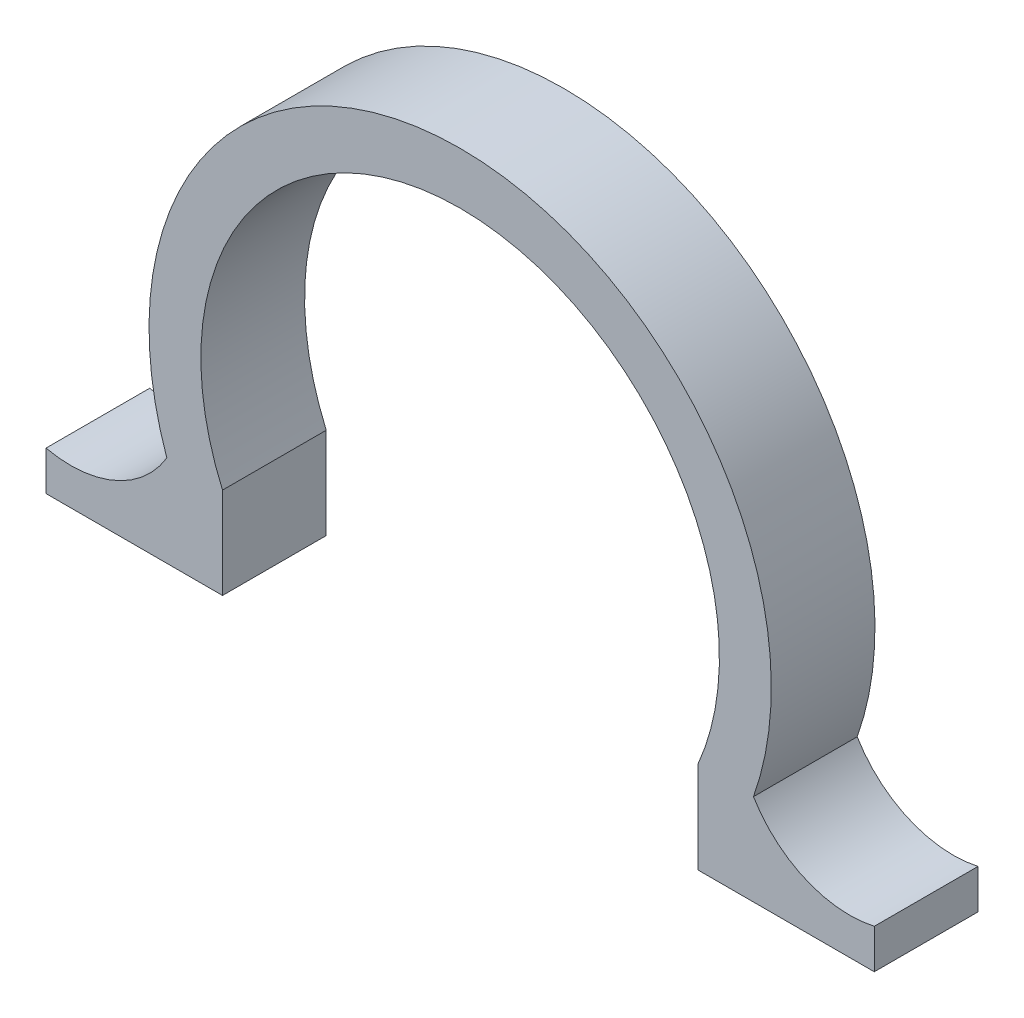
SolidWorks part; units mm, degrees
material "PE High Density"
ref_plane "Front Plane" through (0, 0, 0) normal (0, 0, 1) x (1, 0, 0)
ref_plane "Top Plane" through (0, 0, 0) normal (0, 1, 0) x (1, 0, 0)
ref_plane "Right Plane" through (0, 0, 0) normal (1, 0, 0) x (0, 0, -1)
sketch "Sketch3" plane through (0, 0, 0) normal (0, 0, 1) x (1, 0, 0)
  line L0 (-35.921, -12.7) -> (-29.0994, -12.7)
  line L1 (29.0994, -12.7) -> (35.921, -12.7)
  arc A0 (29.0994, -12.7) -> (-29.0994, -12.7) centre (0, 0) ccw
  arc A1 (35.921, -12.7) -> (-35.921, -12.7) centre (0, 0) ccw
  dimension "D1" = 63.5
  dimension "D2" = 76.2
  dimension "D3" = 50.8
extrude "Boss-Extrude2" add sketch "Sketch3" along normal blind 12.7
sketch "Sketch4" plane through (0, 0, 0) normal (0, 0, -1) x (-1, 0, 0)
  line L0 (-29.0994, -12.7) -> (-29.0994, -23.876)
  line L1 (-29.0994, -23.876) -> (-50.7148, -23.876)
  line L2 (-50.7148, -23.876) -> (-50.7148, -19.05)
  line L3 (29.0994, -12.7) -> (29.0994, -23.876)
  line L4 (29.0994, -23.876) -> (50.7148, -23.876)
  line L5 (50.7148, -23.876) -> (50.7148, -19.05)
  line L6 (29.0994, -12.7) -> (35.921, -12.7)
  line L7 (-35.921, -12.7) -> (-29.0994, -12.7)
  arc A0 (-50.7148, -19.05) -> (-35.921, -12.7) centre (-47.6983, -5.6698) ccw
  arc A1 (50.7148, -19.05) -> (35.921, -12.7) centre (47.6983, -5.6698) cw
  dimension "D4" = 13.716
  dimension "D8" = 13.716
  dimension "D1" = 21.6154
  dimension "D2" = 11.176
  dimension "D3" = 4.826
  dimension "D5" = 11.176
  dimension "D6" = 21.6154
  dimension "D7" = 4.826
extrude "Boss-Extrude3" add sketch "Sketch4" against normal blind 12.7
